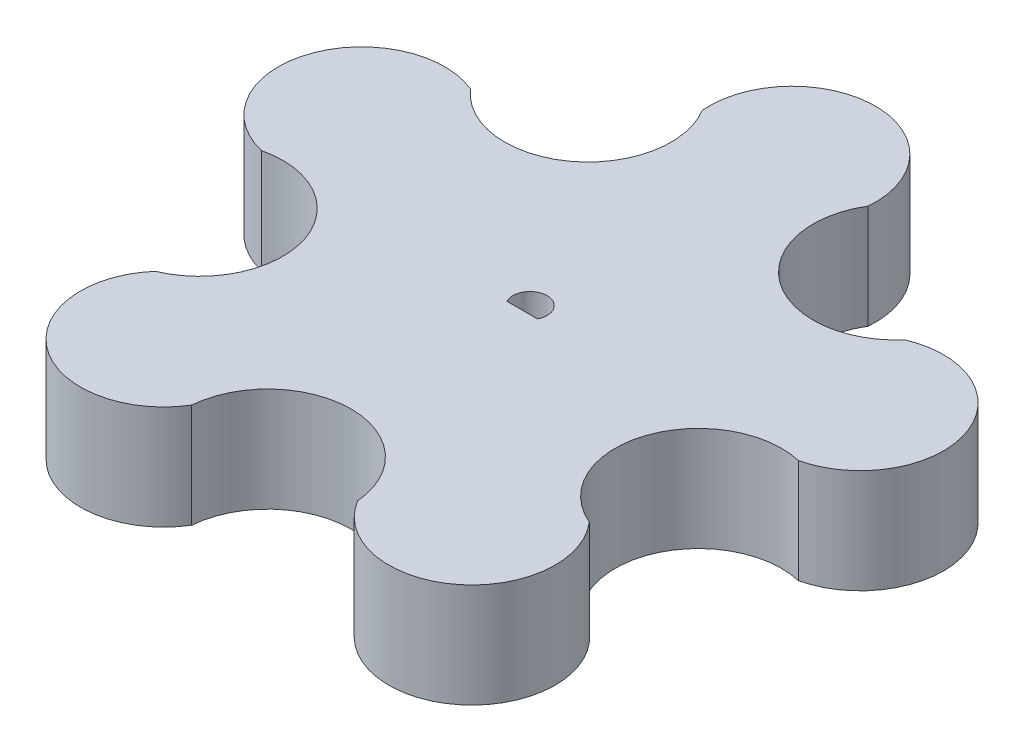
SolidWorks part; units mm, degrees
ref_plane "Front Plane" through (0, 0, 0) normal (0, 0, 1) x (1, 0, 0)
ref_plane "Top Plane" through (0, 0, 0) normal (0, 1, 0) x (1, 0, 0)
ref_plane "Right Plane" through (0, 0, 0) normal (1, 0, 0) x (0, 0, -1)
sketch "Sketch5" plane through (0, 0, 0) normal (0, 1, 0) x (1, 0, 0)
  line L0 (58.7276, 31.6513) -> (58.7276, 14.7019) construction
  line L1 (68.6902, 28.4142) -> (58.7276, 14.7019) construction
  line L2 (74.8474, 19.9395) -> (58.7276, 14.7019) construction
  line L3 (74.8474, 9.4642) -> (58.7276, 14.7019) construction
  line L4 (68.6902, 0.9895) -> (58.7276, 14.7019) construction
  line L5 (58.7276, -2.2476) -> (58.7276, 14.7019) construction
  line L6 (48.7649, 0.9895) -> (58.7276, 14.7019) construction
  line L7 (42.6077, 9.4642) -> (58.7276, 14.7019) construction
  line L8 (42.6077, 19.9395) -> (58.7276, 14.7019) construction
  line L9 (48.7649, 28.4142) -> (58.7276, 14.7019) construction
  arc A0 (63.7901, 30.2827) -> (53.6651, 30.2827) centre (58.7276, 30.7039) ccw
  arc A1 (63.7901, 30.2827) -> (71.9814, 24.3313) centre (68.1333, 27.6478) ccw
  arc A2 (75.1102, 14.7019) -> (71.9814, 24.3313) centre (73.9464, 19.6468) ccw
  arc A3 (75.1102, 14.7019) -> (71.9814, 5.0724) centre (73.9464, 9.757) ccw
  arc A4 (63.7901, -0.8789) -> (71.9814, 5.0724) centre (68.1333, 1.756) ccw
  arc A5 (63.7901, -0.8789) -> (53.6651, -0.8789) centre (58.7276, -1.3001) ccw
  arc A6 (45.4737, 5.0724) -> (53.6651, -0.8789) centre (49.3218, 1.756) ccw
  arc A7 (45.4737, 5.0724) -> (42.3449, 14.7019) centre (43.5088, 9.757) ccw
  arc A8 (45.4737, 24.3313) -> (42.3449, 14.7019) centre (43.5088, 19.6468) ccw
  arc A9 (45.4737, 24.3313) -> (53.6651, 30.2827) centre (49.3218, 27.6478) ccw
  point P34 (58.7276, 14.7019)
  dimension "D1" = 10
extrude "Boss-Extrude1" add sketch "Sketch5" along normal blind 6.35
sketch "Sketch6" plane through (0, 0, 0) normal (0, 1, 0) x (1, 0, 0)
  line L0 (58.7276, 4.4323) -> (69.0712, 12.3405) construction
  line L1 (69.2986, 12.9027) -> (65.4012, 24.9715) construction
  line L2 (65.4012, 24.9715) -> (52.054, 24.9715) construction
  line L3 (52.054, 24.9715) -> (48.8318, 12.2623) construction
  line L4 (48.8318, 12.2623) -> (58.7276, 4.4323) construction
  line L5 (58.7276, 24.9715) -> (58.7276, 4.4323) construction
  line L6 (58.7276, 15.7496) -> (58.7276, 14.2256) construction
  line L7 (57.7943, 14.2256) -> (59.6608, 14.2256)
  arc A0 (59.6608, 14.2256) -> (57.7943, 14.2256) centre (58.7276, 14.7019) ccw
extrude "Cut-Extrude1" cut sketch "Sketch6" along normal through all
